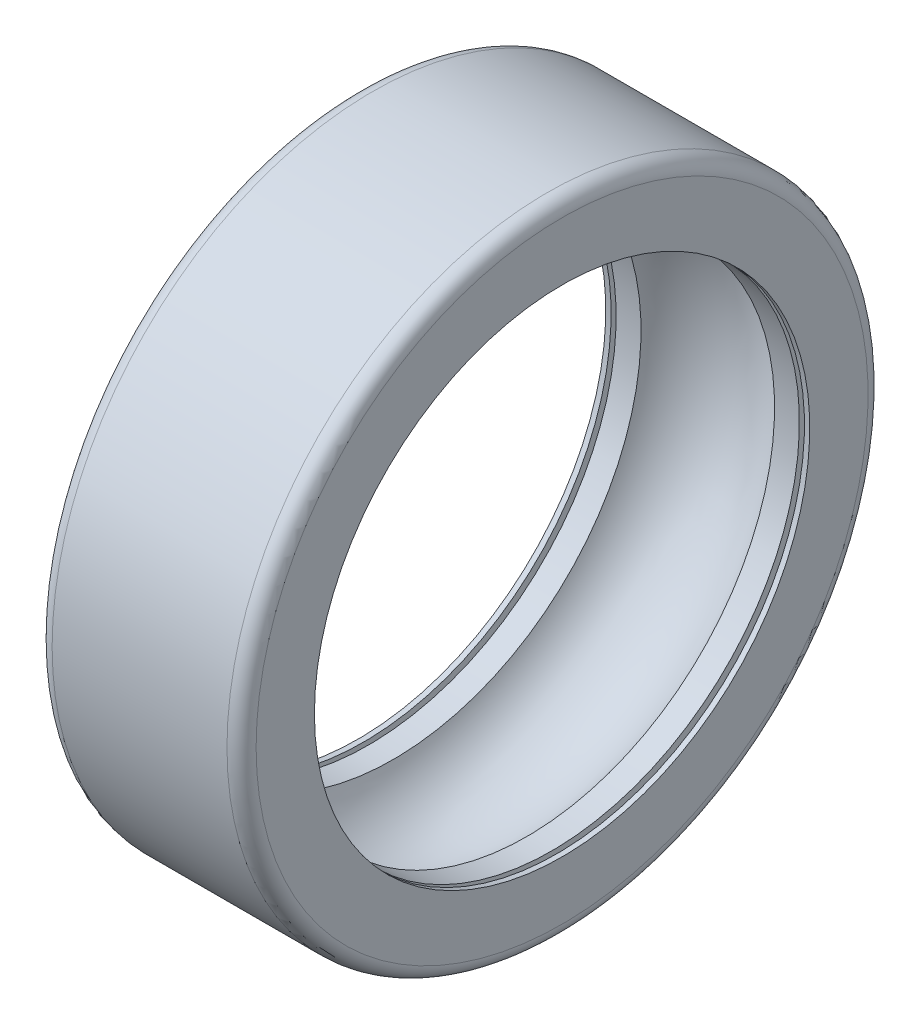
SolidWorks part; units mm, degrees
ref_plane "Plan de face" through (0, 0, 0) normal (0, 0, 1) x (1, 0, 0)
ref_plane "Plan de dessus" through (0, 0, 0) normal (0, 1, 0) x (1, 0, 0)
ref_plane "Plan de droite" through (0, 0, 0) normal (1, 0, 0) x (0, 0, -1)
sketch "Esquisse1" plane through (0, 0, 0) normal (0, 0, 1) x (1, 0, 0)
  line L0 (0, 0) -> (7, 0) construction
  line L1 (12.6319, 11) -> (18.6319, 11)
  line L2 (12.1319, 10.5) -> (12.1319, 8.5)
  line L3 (12.1319, 8.5) -> (12.3147, 8.5)
  line L4 (19.1319, 10.5) -> (19.1319, 8.5)
  line L5 (12.1319, 6.5) -> (12.1319, -6.5) construction
  line L6 (17.9232, 8.5) -> (18.7764, 8.5)
  line L7 (8.8007, 0) -> (22.3746, 0) construction
  line L8 (12.3147, 8.5) -> (12.3147, 8.804)
  line L9 (12.3147, 8.804) -> (12.4875, 8.804)
  line L10 (12.4875, 8.804) -> (12.4875, 8.5)
  line L11 (12.4875, 8.5) -> (13.3406, 8.5)
  line L12 (15.6319, 7.5) -> (15.6319, 0.902) construction
  line L13 (18.7764, 8.804) -> (18.7764, 8.5)
  line L14 (18.9492, 8.804) -> (18.7764, 8.804)
  line L15 (18.9492, 8.5) -> (18.9492, 8.804)
  line L16 (18.9492, 8.5) -> (19.1319, 8.5)
  arc A0 (17.9232, 8.5) -> (13.3406, 8.5) centre (15.6319, 7.5) ccw
  arc A1 (12.1319, 10.5) -> (12.6319, 11) centre (12.6319, 10.5) cw
  arc A2 (19.1319, 10.5) -> (18.6319, 11) centre (18.6319, 10.5) ccw
  point P13 (12.1319, 11)
  point P16 (19.1319, 11)
  dimension "D4" = 5
  dimension "D7" = 0.5
  dimension "D1" = 11
  dimension "D2" = 2.5
  dimension "D3" = 7
  dimension "D5" = 3.5
  dimension "D6" = 3.5
revolve "Révolution1" add sketch "Esquisse1" angle 360 about L7
